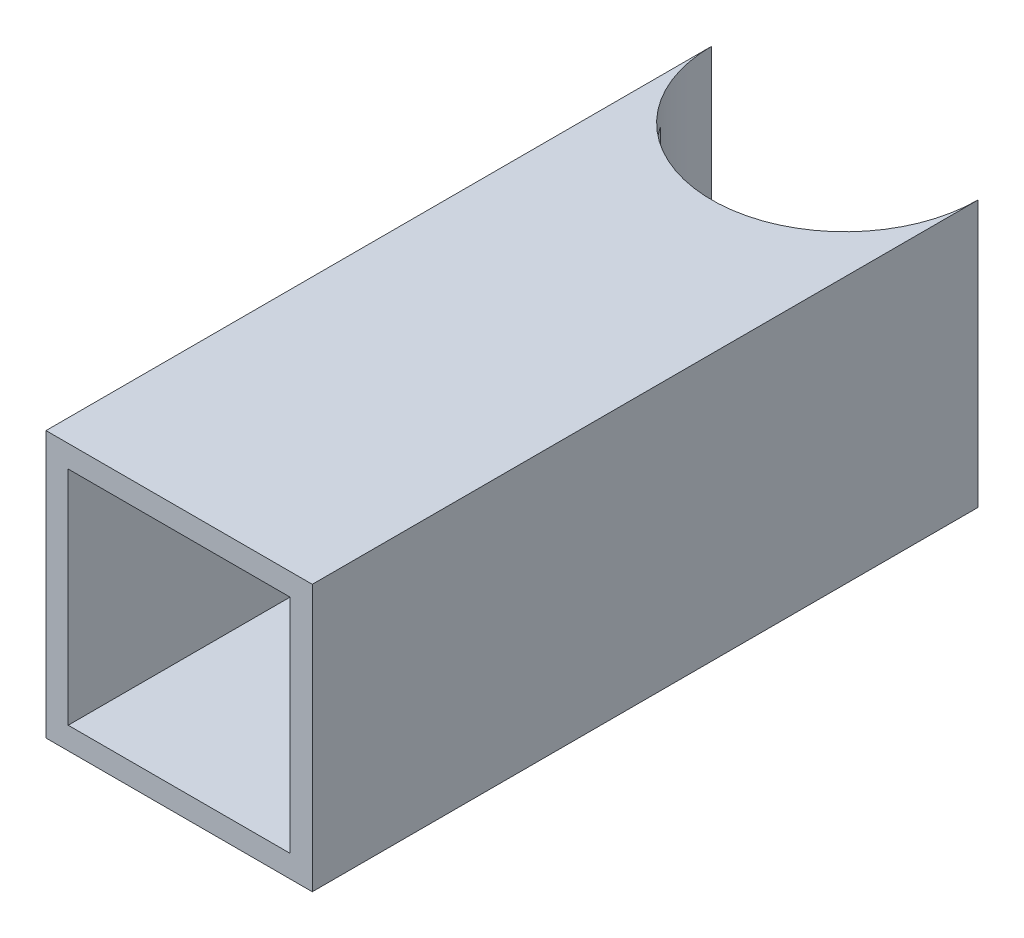
SolidWorks part; units mm, degrees
ref_plane "Front Plane" through (0, 0, 0) normal (0, 0, 1) x (1, 0, 0)
ref_plane "Top Plane" through (0, 0, 0) normal (0, 1, 0) x (1, 0, 0)
ref_plane "Right Plane" through (0, 0, 0) normal (1, 0, 0) x (0, 0, -1)
sketch "Sketch1" plane through (0, 0, 0) normal (0, 0, 1) x (1, 0, 0)
  line L1 (-15, -15) -> (15, -15)
  line L2 (-15, -15) -> (-15, 15)
  line L3 (-15, 15) -> (15, 15)
  line L4 (15, -15) -> (15, 15)
  line L5 (-15, -15) -> (15, 15) construction
  line L6 (-15, 15) -> (15, -15) construction
  line L7 (-12.5, -12.5) -> (12.5, -12.5)
  line L8 (-12.5, -12.5) -> (-12.5, 12.5)
  line L9 (-12.5, 12.5) -> (12.5, 12.5)
  line L10 (12.5, -12.5) -> (12.5, 12.5)
  line L11 (-12.5, -12.5) -> (12.5, 12.5) construction
  line L12 (-12.5, 12.5) -> (12.5, -12.5) construction
  point P0 (0, 0)
  point P6 (0, 0)
  dimension "D1" = 30
  dimension "D2" = 30
  dimension "D3" = 25
  dimension "D4" = 25
extrude "Boss-Extrude1" add sketch "Sketch1" along normal blind 75
sketch "Sketch2" plane through (0, -15, 0) normal (0, -1, 0) x (1, 0, 0)
  circle A0 centre (0, 0) radius 15
  dimension "D1" = 30
extrude "Cut-Extrude1" cut sketch "Sketch2" against normal through all
